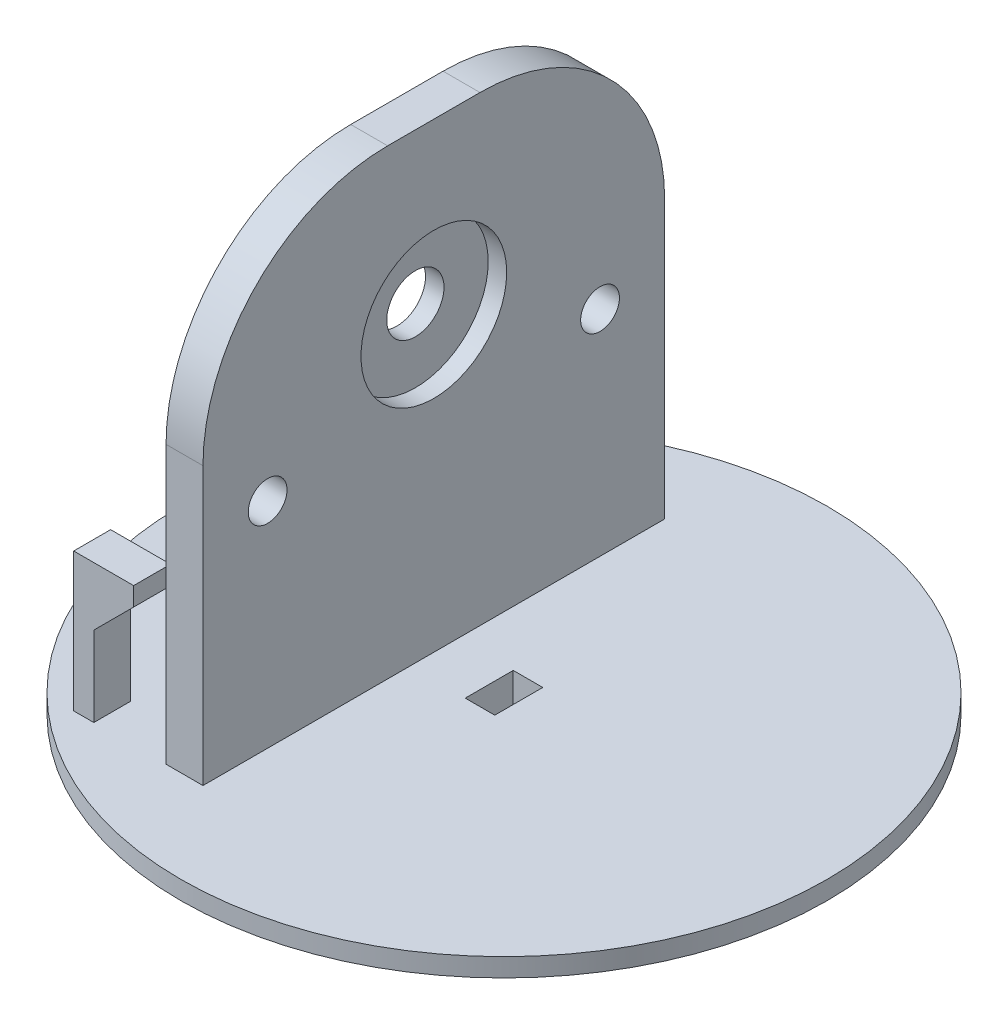
SolidWorks part; units mm, degrees
ref_plane "Front Plane" through (0, 0, 0) normal (0, 0, 1) x (1, 0, 0)
ref_plane "Top Plane" through (0, 0, 0) normal (0, 1, 0) x (1, 0, 0)
ref_plane "Right Plane" through (0, 0, 0) normal (1, 0, 0) x (0, 0, -1)
sketch "Sketch1" plane through (0, 0, 0) normal (0, 1, 0) x (1, 0, 0)
  line L1 (-1.6, -2.6) -> (1.6, -2.6)
  line L2 (-1.6, -2.6) -> (-1.6, 2.6)
  line L3 (-1.6, 2.6) -> (1.6, 2.6)
  line L4 (1.6, -2.6) -> (1.6, 2.6)
  line L5 (-1.6, -2.6) -> (1.6, 2.6) construction
  line L6 (-1.6, 2.6) -> (1.6, -2.6) construction
  circle A0 centre (0, 0) radius 35
  dimension "D1" = 70
  dimension "D2" = 3.2
  dimension "D3" = 5.2
extrude "Boss-Extrude1" add sketch "Sketch1" along normal blind 2
sketch "Sketch2" plane through (0, 0, 0) normal (0, -1, 0) x (1, 0, 0)
  line L0 (1.6, 2.6) -> (1.6, -2.6) construction
  line L1 (1.6, 2.6) -> (1.6, -2.6)
  line L2 (1.6, -2.6) -> (-1.6, -2.6) construction
  line L3 (-1.6, -2.6) -> (-1.6, 2.6) construction
  line L4 (-1.6, 2.6) -> (1.6, 2.6) construction
  line L5 (1.6, -2.6) -> (-1.6, -2.6)
  line L6 (-1.6, -2.6) -> (-1.6, 2.6)
  line L7 (-1.6, 2.6) -> (1.6, 2.6)
  line L8 (-3.6, -4.6) -> (-3.6, 4.6)
  line L9 (-3.6, 4.6) -> (3.6, 4.6)
  line L10 (3.6, 4.6) -> (3.6, -4.6)
  line L11 (3.6, -4.6) -> (-3.6, -4.6)
  dimension "D1" = 2
extrude "Boss-Extrude2" add sketch "Sketch2" along normal blind 3
sketch "Sketch3" plane through (0, 2, 0) normal (0, 1, 0) x (1, 0, 0)
  line L0 (-1.6, 2.6) -> (-1.6, -2.6) construction
  line L1 (-7.6, 25) -> (-11.6, 25)
  line L2 (-7.6, 25) -> (-7.6, -25)
  line L3 (-7.6, -25) -> (-11.6, -25)
  line L4 (-11.6, 25) -> (-11.6, -25)
  line L5 (-7.6, 25) -> (-11.6, -25) construction
  line L6 (-7.6, -25) -> (-11.6, 25) construction
  line L7 (-2.75, 0) -> (2.75, 0) construction
  point P0 (-9.6, 0)
  dimension "D1" = 4
  dimension "D2" = 6
  dimension "D3" = 50
  dimension "D4" = 25
extrude "Boss-Extrude3" add sketch "Sketch3" along normal blind 50
sketch "Sketch4" plane through (-7.6, 0, 0) normal (1, 0, 0) x (0, 0, -1)
  line L0 (0, 52) -> (0, 2.0887) construction
  line L1 (-25, 52) -> (25, 52) construction
  circle A0 centre (0, 33.6913) radius 3.1
  circle A1 centre (-18, 25.1913) radius 2.1
  circle A2 centre (18, 25.1913) radius 2.1
  dimension "D1" = 6.2
  dimension "D2" = 4.2
  dimension "D3" = 18
  dimension "D4" = 8.5
extrude "Cut-Extrude1" cut sketch "Sketch4" against normal blind 50
fillet "Fillet1" radius 20 2 edges at (-9.6, 52, -25) (-9.6, 52, 25)
sketch "Sketch6" plane through (0, 2, 0) normal (0, 1, 0) x (1, 0, 0)
  line L1 (-11.6, -25) -> (-21.6, -25)
  line L2 (-11.6, -25) -> (-11.6, -21)
  line L3 (-11.6, -21) -> (-21.6, -21)
  line L4 (-21.6, -25) -> (-21.6, -21)
  dimension "D1" = 4
  dimension "D2" = 10
extrude "Boss-Extrude4" add sketch "Sketch6" along normal blind 15
sketch "Sketch7" plane through (0, 0, 25) normal (0, 0, 1) x (1, 0, 0)
  line L0 (-11.6, 2) -> (-11.6, 17)
  line L1 (-21.6, 2) -> (-7.6, 2) construction
  line L2 (-21.6, 17) -> (-11.6, 17) construction
  line L3 (-11.6, 32) -> (-11.6, 17) construction
  line L4 (-11.6, 17) -> (-15.1105, 17)
  line L5 (-15.1105, 17) -> (-15.1105, 14.9805)
  line L6 (-15.1105, 14.9805) -> (-19.4214, 10.6696)
  line L7 (-19.4214, 10.6696) -> (-19.4214, 2)
  line L8 (-19.4214, 2) -> (-11.6, 2)
  dimension "D1" = 135
extrude "Cut-Extrude2" cut sketch "Sketch7" against normal blind 15
sketch "Sketch8" plane through (-7.6, 0, 0) normal (1, 0, 0) x (0, 0, -1)
  circle A0 centre (0, 33.6913) radius 7.8891
  circle A1 centre (0, 33.6913) radius 6.8891 construction
  dimension "D1" = 1
extrude "Cut-Extrude3" cut sketch "Sketch8" against normal blind 2
sketch "Sketch9" plane through (0, -3, 0) normal (0, -1, 0) x (1, 0, 0)
  line L0 (-3.6, -4.6) -> (3.6, -4.6) construction
  line L1 (3.6, -4.6) -> (3.6, 4.6) construction
  line L2 (3.6, 4.6) -> (-3.6, 4.6) construction
  line L3 (-3.6, 4.6) -> (-3.6, -4.6) construction
  line L4 (-3.6, -4.6) -> (3.6, -4.6)
  line L5 (3.6, -4.6) -> (3.6, 4.6)
  line L6 (3.6, 4.6) -> (-3.6, 4.6)
  line L7 (-3.6, 4.6) -> (-3.6, -4.6)
  circle A0 centre (0, 0) radius 10
  dimension "D1" = 20
extrude "Boss-Extrude5" add sketch "Sketch9" against normal up to surface (3 mm away) up to face at (0, 0, 35)
